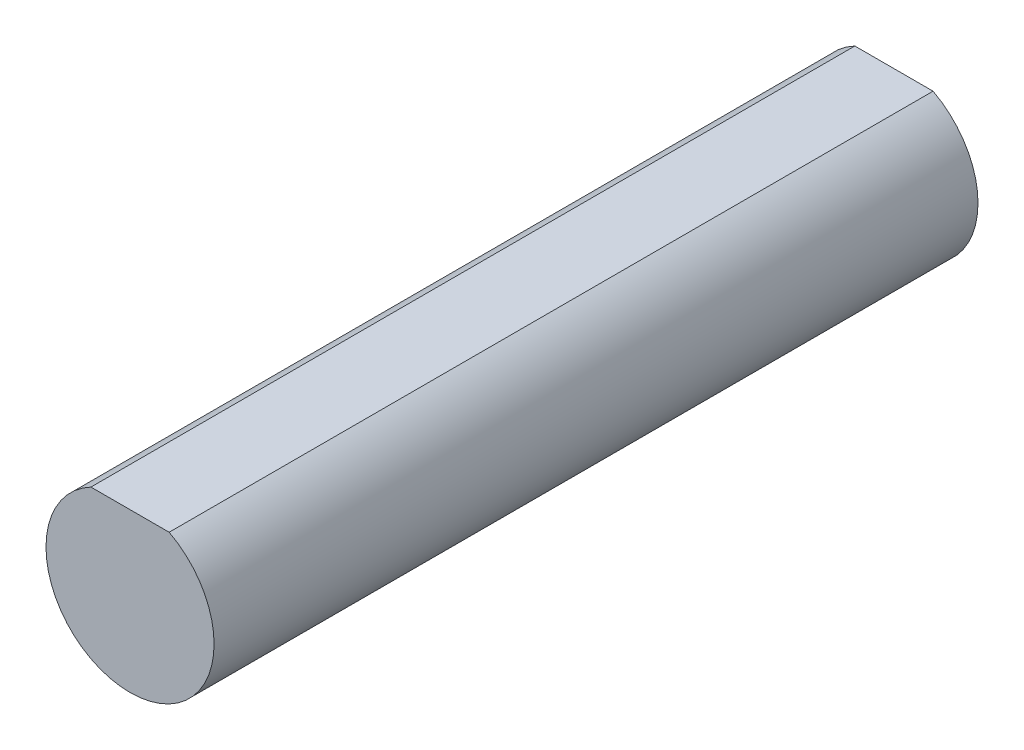
SolidWorks part; units mm, degrees
ref_plane "Front Plane" through (0, 0, 0) normal (0, 0, 1) x (1, 0, 0)
ref_plane "Top Plane" through (0, 0, 0) normal (0, 1, 0) x (1, 0, 0)
ref_plane "Right Plane" through (0, 0, 0) normal (1, 0, 0) x (0, 0, -1)
sketch "Sketch1" plane through (0, 0, 0) normal (0, 0, 1) x (1, 0, 0)
  line L0 (-1.1826, 2.2479) -> (1.1826, 2.2479)
  circle A0 centre (0, 0) radius 2.54
  arc A1 (-1.1826, 2.2479) -> (1.1826, 2.2479) centre (0, 0) cw
  dimension "D1" = 5.08
  dimension "D2" = 2.2479
extrude "Boss-Extrude1" add sketch "Sketch1" along normal blind 23.0886 contours A0 | A1 L0
sketch "Sketch2" plane through (0, 0, 0) normal (0, 0, -1) x (-1, 0, 0)
  line L0 (-1.1826, 2.2479) -> (1.1826, 2.2479)
  arc A0 (-1.1826, 2.2479) -> (1.1826, 2.2479) centre (0, 0) cw
  circle A1 centre (0, 0) radius 2.54 construction
extrude "Cut-Extrude1" cut sketch "Sketch2" against normal blind 23.0886
